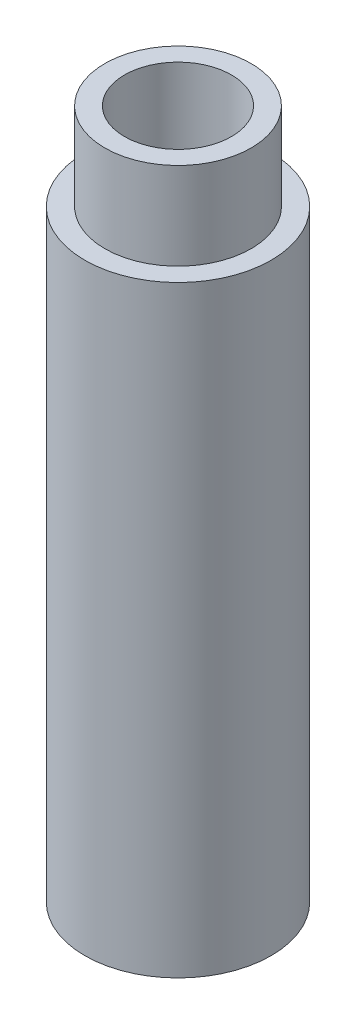
SolidWorks part; units mm, degrees
ref_plane "Front Plane" through (0, 0, 0) normal (0, 0, 1) x (1, 0, 0)
ref_plane "Top Plane" through (0, 0, 0) normal (0, 1, 0) x (1, 0, 0)
ref_plane "Right Plane" through (0, 0, 0) normal (1, 0, 0) x (0, 0, -1)
sketch "Sketch1" plane through (0, 0, 0) normal (0, 1, 0) x (1, 0, 0)
  circle A0 centre (0, 0) radius 8.275
  dimension "D1" = 16.55
extrude "Boss-Extrude1" add sketch "Sketch1" along normal blind 61.25
sketch "Sketch2" plane through (0, 61.25, 0) normal (0, 1, 0) x (1, 0, 0)
  circle A0 centre (0, 0) radius 6.5
  circle A1 centre (0, 0) radius 4.75
  circle A2 centre (0, 0) radius 8.275 construction
  circle A3 centre (0, 0) radius 8.275
  circle M2 centre (0, 0) radius 8.275
  dimension "D1" = 13
  dimension "D2" = 9.5
extrude "Cut-Extrude1" cut sketch "Sketch2" against normal blind 7.75 contours A0 M2 | A1
sketch "Sketch3" plane through (0, 53.5, 0) normal (0, 1, 0) x (1, 0, 0)
  circle A1 centre (0, 0) radius 4.75
  circle A2 centre (0, 0) radius 4.75
  dimension "D1" = 0
extrude "Cut-Extrude3" cut sketch "Sketch3" along direction (0, 1, 0) on the side against the normal offset from surface (51.5 mm away) 2
